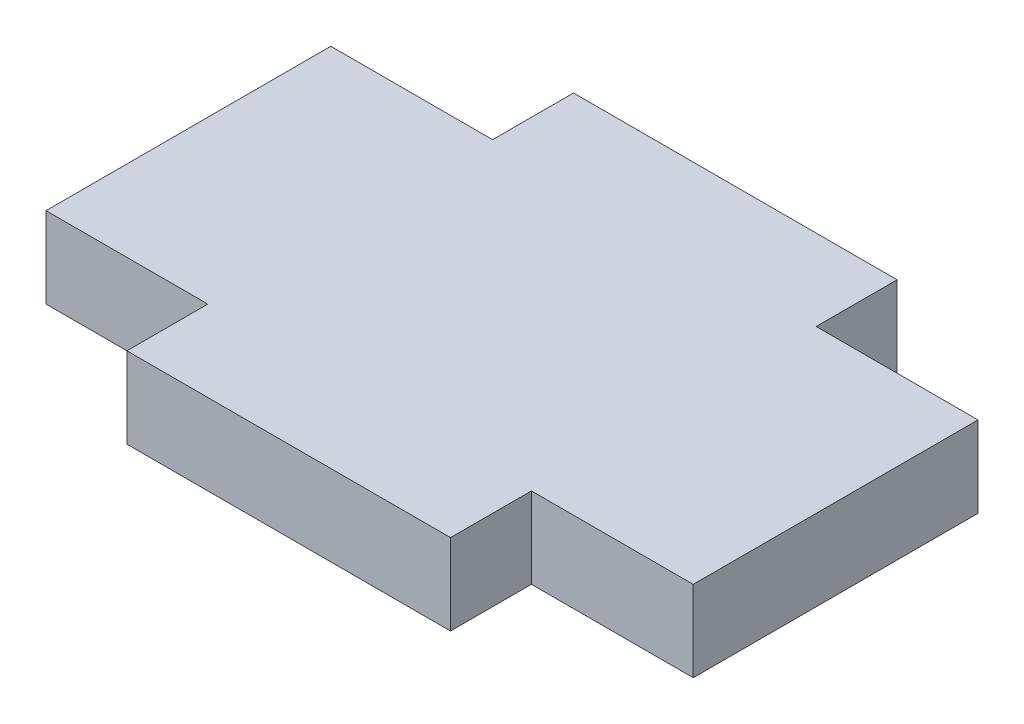
SolidWorks part; units mm, degrees
ref_plane "Front Plane" through (0, 0, 0) normal (0, 0, 1) x (1, 0, 0)
ref_plane "Top Plane" through (0, 0, 0) normal (0, 1, 0) x (1, 0, 0)
ref_plane "Right Plane" through (0, 0, 0) normal (1, 0, 0) x (0, 0, -1)
sketch "Sketch1" plane through (0, 0, 0) normal (0, 1, 0) x (1, 0, 0)
  line L0 (12.7, 11.176) -> (12.7, 0) construction
  line L1 (0, 0) -> (25.4, 0)
  line L2 (0, 0) -> (0, 11.176)
  line L3 (0, 11.176) -> (25.4, 11.176)
  line L4 (25.4, 0) -> (25.4, 11.176)
  line L5 (19.05, 11.176) -> (19.05, 14.351)
  line L6 (19.05, 11.176) -> (6.35, 11.176)
  line L7 (12.7, 11.176) -> (12.7, 14.351)
  line L8 (19.05, 14.351) -> (6.35, 14.351)
  line L9 (6.35, 11.176) -> (6.35, 14.351)
  line L10 (0, 5.588) -> (25.4, 5.588) construction
  line L11 (19.05, 0) -> (19.05, -3.175)
  line L12 (19.05, 0) -> (6.35, 0)
  line L13 (6.35, 0) -> (6.35, -3.175)
  line L14 (19.05, -3.175) -> (6.35, -3.175)
  dimension "D1" = 11.176
  dimension "D2" = 25.4
  dimension "D3" = 3.175
  dimension "D4" = 6.35
extrude "Boss-Extrude1" add sketch "Sketch1" along normal blind 3.175 contours L1 L4 L3 L6 L2 | L14 L11 L1 L13 | L5 L8 L7 L6 | L9 L3 L7 L8
